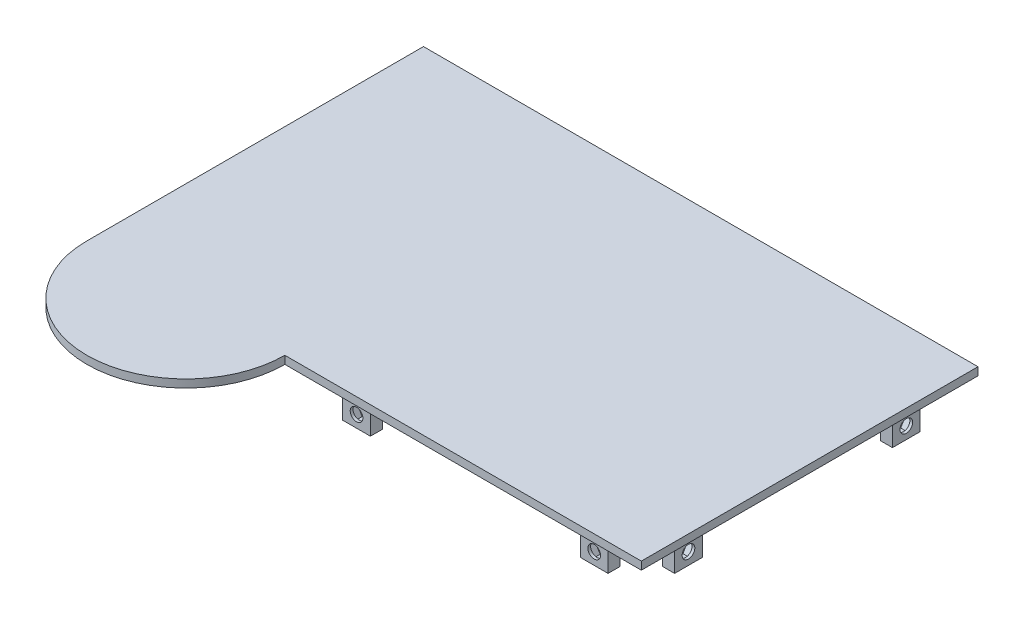
SolidWorks part; units mm, degrees
ref_plane "Ön Düzlem" through (0, 0, 0) normal (0, 0, 1) x (1, 0, 0)
ref_plane "Üst Düzlem" through (0, 0, 0) normal (0, 1, 0) x (1, 0, 0)
ref_plane "Sağ Düzlem" through (0, 0, 0) normal (1, 0, 0) x (0, 0, -1)
sketch "Çizim1" plane through (0, 0, 0) normal (0, 1, 0) x (1, 0, 0)
  line L1 (50, 0) -> (140, 0)
  line L2 (0, 0) -> (0, 85)
  line L3 (0, 85) -> (140, 85)
  line L4 (140, 0) -> (140, 85)
  arc A0 (0, 0) -> (50, 0) centre (25, 0) ccw
  dimension "D3" = 50
  dimension "D1" = 140
  dimension "D2" = 85
extrude "Yükseklik-Ekstrüzyon1" add sketch "Çizim1" along normal blind 2
sketch "Çizim2" plane through (0, 0, 0) normal (0, -1, 0) x (1, 0, 0)
  line L0 (140, -85) -> (0, -85) construction
  line L1 (11.5, -81.9) -> (18.5, -81.9)
  line L2 (11.5, -81.9) -> (11.5, -78.9)
  line L3 (11.5, -78.9) -> (18.5, -78.9)
  line L4 (18.5, -81.9) -> (18.5, -78.9)
  line L5 (15, -78.9) -> (15, -81.9) construction
  line L6 (0, -85) -> (0, 0) construction
  line L7 (121.5, -81.9) -> (121.5, -78.9)
  line L8 (121.5, -81.9) -> (128.5, -81.9)
  line L9 (128.5, -81.9) -> (128.5, -78.9)
  line L10 (121.5, -78.9) -> (128.5, -78.9)
  line L11 (6.1, -70) -> (3.1, -70) construction
  line L12 (3.1, -66.5) -> (6.1, -66.5)
  line L13 (3.1, -66.5) -> (3.1, -73.5)
  line L14 (3.1, -73.5) -> (6.1, -73.5)
  line L15 (6.1, -66.5) -> (6.1, -73.5)
  line L16 (3.1, -11.5) -> (3.1, -18.5)
  line L17 (3.1, -11.5) -> (6.1, -11.5)
  line L18 (6.1, -11.5) -> (6.1, -18.5)
  line L19 (3.1, -18.5) -> (6.1, -18.5)
  line L20 (70, -85) -> (70, 0) construction
  line L21 (50, 0) -> (140, 0) construction
  line L22 (136.9, -73.5) -> (133.9, -73.5)
  line L23 (133.9, -66.5) -> (133.9, -73.5)
  line L24 (136.9, -66.5) -> (133.9, -66.5)
  line L25 (136.9, -66.5) -> (136.9, -73.5)
  line L26 (136.9, -11.5) -> (133.9, -11.5)
  line L27 (133.9, -11.5) -> (133.9, -18.5)
  line L28 (136.9, -18.5) -> (133.9, -18.5)
  line L29 (136.9, -11.5) -> (136.9, -18.5)
  line L30 (140, -42.5) -> (0, -42.5) construction
  line L31 (140, 0) -> (140, -85) construction
  line L32 (121.5, -3.1) -> (128.5, -3.1)
  line L33 (128.5, -3.1) -> (128.5, -6.1)
  line L34 (121.5, -6.1) -> (128.5, -6.1)
  line L35 (121.5, -3.1) -> (121.5, -6.1)
  line L36 (61.5, -3.1) -> (68.5, -3.1)
  line L37 (68.5, -3.1) -> (68.5, -6.1)
  line L38 (61.5, -6.1) -> (68.5, -6.1)
  line L39 (61.5, -3.1) -> (61.5, -6.1)
  dimension "D1" = 3
  dimension "D2" = 7
  dimension "D3" = 3.1
  dimension "D4" = 15
  dimension "D5" = 2
  dimension "D6" = 3
  dimension "D7" = 7
  dimension "D8" = 3.1
  dimension "D9" = 15
  dimension "D10" = 2
  dimension "D11" = 2
extrude "Yükseklik-Ekstrüzyon2" add sketch "Çizim2" along normal blind 8
sketch "Çizim3" plane through (0, 0, -6.1) normal (0, 0, -1) x (-1, 0, 0)
  line L1 (-68.5, -8) -> (-68.5, 0) construction
  line L2 (-68.1754, -5) -> (-66.5877, -7.75)
  line L9 (-66.5877, -7.75) -> (-63.4123, -7.75)
  line L10 (-63.4123, -7.75) -> (-61.8246, -5)
  line L11 (-61.8246, -5) -> (-63.4123, -2.25)
  line L12 (-63.4123, -2.25) -> (-66.5877, -2.25)
  line L13 (-66.5877, -2.25) -> (-68.1754, -5)
  line L15 (-61.5, 0) -> (-68.5, 0) construction
  circle A0 centre (-65, -5) radius 2.75 construction
  point P16 (-64.3482, 0)
  dimension "D1" = 5.5
  dimension "D2" = 3.5
  dimension "D3" = 5
extrude "Kes-Ekstrüzyon1" cut sketch "Çizim3" against normal blind 2.3
sketch "Çizim4" plane through (0, 0, -6.1) normal (0, 0, -1) x (-1, 0, 0)
  line L0 (-121.5, 0) -> (-128.5, 0) construction
  line L1 (-128.5, -8) -> (-128.5, 0) construction
  line L3 (-126.4849, -2.1932) -> (-128.1733, -4.8825)
  line L4 (-128.1733, -4.8825) -> (-126.6883, -7.6894)
  line L5 (-126.6883, -7.6894) -> (-123.5151, -7.8068)
  line L6 (-123.5151, -7.8068) -> (-121.8267, -5.1175)
  line L7 (-121.8267, -5.1175) -> (-123.3117, -2.3106)
  line L8 (-123.3117, -2.3106) -> (-126.4849, -2.1932)
  circle A0 centre (-125, -5) radius 2.75 construction
  point P8 (-127.4308, -6.286)
  dimension "D1" = 5.5
  dimension "D2" = 5
  dimension "D3" = 3.5
extrude "Kes-Ekstrüzyon2" cut sketch "Çizim4" against normal blind 2.3
sketch "Çizim5" plane through (6.1, 0, 0) normal (1, 0, 0) x (0, 0, -1)
  line L0 (18.5, -8) -> (18.5, 0) construction
  line L1 (13.4578, -2.2242) -> (11.825, -4.9477)
  line L2 (11.825, -4.9477) -> (13.3672, -7.7235)
  line L3 (13.3672, -7.7235) -> (16.5422, -7.7758)
  line L4 (16.5422, -7.7758) -> (18.175, -5.0523)
  line L5 (18.175, -5.0523) -> (16.6328, -2.2765)
  line L6 (16.6328, -2.2765) -> (13.4578, -2.2242)
  line L7 (18.5, 0) -> (11.5, 0) construction
  circle A0 centre (15, -5) radius 2.75 construction
  dimension "D1" = 5.5
  dimension "D2" = 3.5
  dimension "D3" = 5
extrude "Kes-Ekstrüzyon3" cut sketch "Çizim5" against normal blind 2.3
sketch "Çizim6" plane through (6.1, 0, 0) normal (1, 0, 0) x (0, 0, -1)
  line L0 (73.5, -8) -> (73.5, 0) construction
  line L1 (68.4168, -2.2474) -> (66.8246, -4.9948)
  line L2 (66.8246, -4.9948) -> (68.4078, -7.7474)
  line L3 (68.4078, -7.7474) -> (71.5832, -7.7526)
  line L4 (71.5832, -7.7526) -> (73.1754, -5.0052)
  line L5 (73.1754, -5.0052) -> (71.5922, -2.2526)
  line L6 (71.5922, -2.2526) -> (68.4168, -2.2474)
  line L7 (73.5, 0) -> (66.5, 0) construction
  circle A0 centre (70, -5) radius 2.75 construction
  point P1 (67.6207, -3.6211)
  dimension "D1" = 5.5
  dimension "D2" = 3.5
  dimension "D3" = 5
extrude "Kes-Ekstrüzyon4" cut sketch "Çizim6" against normal blind 2.3
sketch "Çizim7" plane through (0, 0, -78.9) normal (0, 0, 1) x (1, 0, 0)
  line L0 (18.5, -8) -> (18.5, 0) construction
  line L1 (13.4182, -2.2466) -> (11.8246, -4.9931)
  line L2 (11.8246, -4.9931) -> (13.4063, -7.7466)
  line L3 (13.4063, -7.7466) -> (16.5818, -7.7534)
  line L4 (16.5818, -7.7534) -> (18.1754, -5.0069)
  line L5 (18.1754, -5.0069) -> (16.5937, -2.2534)
  line L6 (16.5937, -2.2534) -> (13.4182, -2.2466)
  line L7 (18.5, 0) -> (11.5, 0) construction
  circle A0 centre (15, -5) radius 2.75 construction
  dimension "D1" = 5.5
  dimension "D2" = 3.5
  dimension "D3" = 5
extrude "Kes-Ekstrüzyon5" cut sketch "Çizim7" against normal blind 2.3
sketch "Çizim9" plane through (133.9, 0, 0) normal (-1, 0, 0) x (0, 0, 1)
  line L0 (-11.5, -8) -> (-11.5, 0) construction
  line L1 (-16.5599, -2.2341) -> (-18.1753, -4.968)
  line L2 (-18.1753, -4.968) -> (-16.6154, -7.7338)
  line L3 (-16.6154, -7.7338) -> (-13.4401, -7.7659)
  line L4 (-13.4401, -7.7659) -> (-11.8247, -5.032)
  line L5 (-11.8247, -5.032) -> (-13.3846, -2.2662)
  line L6 (-13.3846, -2.2662) -> (-16.5599, -2.2341)
  line L7 (-11.5, 0) -> (-18.5, 0) construction
  circle A0 centre (-15, -5) radius 2.75 construction
  dimension "D1" = 5.5
  dimension "D2" = 3.5
  dimension "D3" = 5
extrude "Kes-Ekstrüzyon7" cut sketch "Çizim9" against normal blind 2.3
sketch "Çizim11" plane through (133.9, 0, 0) normal (-1, 0, 0) x (0, 0, 1)
  line L0 (-66.5, -8) -> (-66.5, 0) construction
  line L1 (-71.5877, -2.25) -> (-73.1754, -5)
  line L2 (-73.1754, -5) -> (-71.5877, -7.75)
  line L3 (-71.5877, -7.75) -> (-68.4123, -7.75)
  line L4 (-68.4123, -7.75) -> (-66.8246, -5)
  line L5 (-66.8246, -5) -> (-68.4123, -2.25)
  line L6 (-68.4123, -2.25) -> (-71.5877, -2.25)
  line L7 (-66.5, 0) -> (-73.5, 0) construction
  circle A0 centre (-70, -5) radius 2.75 construction
  dimension "D1" = 5.5
  dimension "D2" = 3.5
  dimension "D3" = 5
extrude "Kes-Ekstrüzyon9" cut sketch "Çizim11" against normal blind 2.3
sketch "Çizim12" plane through (0, 0, -78.9) normal (0, 0, 1) x (1, 0, 0)
  line L0 (128.5, -8) -> (128.5, 0) construction
  line L1 (123.4123, -2.25) -> (121.8246, -5)
  line L2 (121.8246, -5) -> (123.4123, -7.75)
  line L3 (123.4123, -7.75) -> (126.5877, -7.75)
  line L4 (126.5877, -7.75) -> (128.1754, -5)
  line L5 (128.1754, -5) -> (126.5877, -2.25)
  line L6 (126.5877, -2.25) -> (123.4123, -2.25)
  line L7 (128.5, 0) -> (121.5, 0) construction
  circle A0 centre (125, -5) radius 2.75 construction
  point P1 (122.6184, -3.625)
  dimension "D1" = 5.5
  dimension "D2" = 3.5
  dimension "D3" = 5
extrude "Kes-Ekstrüzyon10" cut sketch "Çizim12" against normal blind 2.3
sketch "Çizim15" plane through (0, 0, -3.1) normal (0, 0, 1) x (1, 0, 0)
  line L0 (128.5, -8) -> (128.5, 0) construction
  line L1 (128.5, 0) -> (121.5, 0) construction
  circle A0 centre (125, -5) radius 1.6
  dimension "D1" = 3.5
  dimension "D2" = 5
extrude "Kes-Ekstrüzyon11" cut sketch "Çizim15" against normal blind 5
sketch "Çizim16" plane through (0, 0, -3.1) normal (0, 0, 1) x (1, 0, 0)
  line L0 (68.5, -8) -> (68.5, 0) construction
  line L1 (68.5, 0) -> (61.5, 0) construction
  circle A0 centre (65, -5) radius 1.6
  point P4 (68.5, -4)
  point P5 (0, 0)
  point P7 (64.7208, -4.2119)
  dimension "D1" = 3.5
  dimension "D2" = 5
extrude "Kes-Ekstrüzyon12" cut sketch "Çizim16" against normal blind 5
sketch "Çizim17" plane through (3.1, 0, 0) normal (-1, 0, 0) x (0, 0, 1)
  line L0 (-11.5, -8) -> (-11.5, 0) construction
  line L1 (-11.5, 0) -> (-18.5, 0) construction
  circle A0 centre (-15, -5) radius 1.6
  dimension "D1" = 3.5
  dimension "D2" = 5
extrude "Kes-Ekstrüzyon13" cut sketch "Çizim17" against normal blind 5
sketch "Çizim18" plane through (3.1, 0, 0) normal (-1, 0, 0) x (0, 0, 1)
  line L0 (-66.5, -8) -> (-66.5, 0) construction
  line L1 (-66.5, 0) -> (-73.5, 0) construction
  circle A0 centre (-70, -5) radius 1.6
  dimension "D1" = 3.5
  dimension "D2" = 5
extrude "Kes-Ekstrüzyon14" cut sketch "Çizim18" against normal blind 5
sketch "Çizim19" plane through (0, 0, -81.9) normal (0, 0, -1) x (-1, 0, 0)
  line L0 (-11.5, -8) -> (-11.5, 0) construction
  line L1 (-11.5, 0) -> (-18.5, 0) construction
  circle A0 centre (-15, -5) radius 1.6
  dimension "D1" = 3.5
  dimension "D2" = 5
extrude "Kes-Ekstrüzyon15" cut sketch "Çizim19" against normal blind 5
sketch "Çizim20" plane through (0, 0, -81.9) normal (0, 0, -1) x (-1, 0, 0)
  line L0 (-121.5, -8) -> (-121.5, 0) construction
  line L1 (-121.5, 0) -> (-128.5, 0) construction
  circle A0 centre (-125, -5) radius 1.6
  dimension "D1" = 3.5
  dimension "D2" = 5
extrude "Kes-Ekstrüzyon16" cut sketch "Çizim20" against normal blind 5
sketch "Çizim21" plane through (136.9, 0, 0) normal (1, 0, 0) x (0, 0, -1)
  line L0 (73.5, -8) -> (73.5, 0) construction
  line L1 (73.5, 0) -> (66.5, 0) construction
  circle A0 centre (70, -5) radius 1.6
  dimension "D1" = 3.5
  dimension "D2" = 5
extrude "Kes-Ekstrüzyon17" cut sketch "Çizim21" against normal blind 5
sketch "Çizim22" plane through (136.9, 0, 0) normal (1, 0, 0) x (0, 0, -1)
  line L0 (18.5, -8) -> (18.5, 0) construction
  line L1 (18.5, 0) -> (11.5, 0) construction
  circle A0 centre (15, -5) radius 1.6
  dimension "D1" = 3.5
  dimension "D2" = 5
extrude "Kes-Ekstrüzyon18" cut sketch "Çizim22" against normal blind 5
